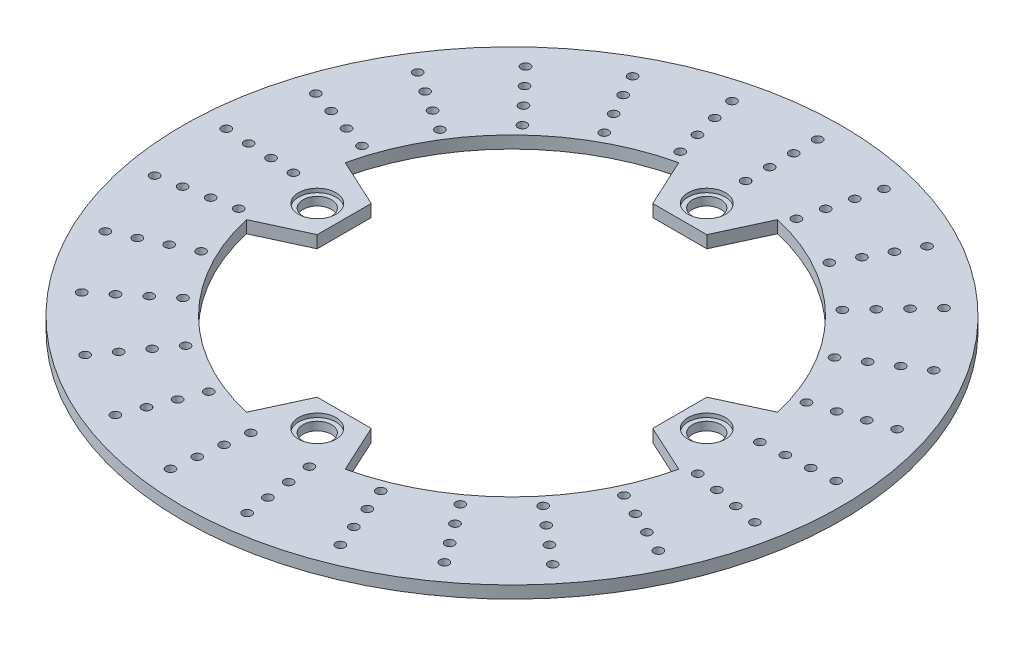
SolidWorks part; units mm, degrees
ref_plane "Front Plane" through (0, 0, 0) normal (0, 0, 1) x (1, 0, 0)
ref_plane "Top Plane" through (0, 0, 0) normal (0, 1, 0) x (1, 0, 0)
ref_plane "Right Plane" through (0, 0, 0) normal (1, 0, 0) x (0, 0, -1)
sketch "Sketch1" plane through (0, 0, 0) normal (0, 1, 0) x (1, 0, 0)
  line L0 (-9.02, 56) -> (9.02, 56)
  line L1 (9.02, 56) -> (16.4701, 72.1438)
  line L2 (-9.02, 56) -> (-16.4701, 72.1438)
  line L3 (0, 0) -> (0, 65) construction
  line L4 (56, 9.02) -> (72.1438, 16.4701)
  line L5 (56, 9.02) -> (56, -9.02)
  line L6 (56, -9.02) -> (72.1438, -16.4701)
  line L7 (9.02, -56) -> (16.4701, -72.1438)
  line L8 (9.02, -56) -> (-9.02, -56)
  line L9 (-9.02, -56) -> (-16.4701, -72.1438)
  line L10 (-56, -9.02) -> (-72.1438, -16.4701)
  line L11 (-56, -9.02) -> (-56, 9.02)
  line L12 (-56, 9.02) -> (-72.1438, 16.4701)
  circle A0 centre (0, 0) radius 110
  arc A1 (-16.4701, 72.1438) -> (-72.1438, 16.4701) centre (0, 0) ccw
  circle A2 centre (0, 65) radius 4.75
  circle A3 centre (65, 0) radius 4.75
  circle A4 centre (0, -65) radius 4.75
  circle A5 centre (-65, 0) radius 4.75
  arc A6 (72.1438, 16.4701) -> (16.4701, 72.1438) centre (0, 0) ccw
  arc A7 (-72.1438, -16.4701) -> (-16.4701, -72.1438) centre (0, 0) ccw
  arc A8 (16.4701, -72.1438) -> (72.1438, -16.4701) centre (0, 0) ccw
  point P6 (0, 0)
  point P10 (0, 0)
  point P11 (0, 56)
  point P34 (0, 0)
  dimension "D1" = 220
  dimension "D2" = 148
  dimension "D4" = 9.5
  dimension "D3" = 65
  dimension "D5" = 56
  dimension "D6" = 4
  dimension "D7" = 17.78
  dimension "D8" = 18.04
  dimension "D9" = 17.78
extrude "Boss-Extrude1" add sketch "Sketch1" along normal blind 4.1
sketch "Sketch3" plane through (0, 0, 0) normal (0, 1, 0) x (1, 0, 0)
  line L0 (0, 0) -> (0, 110) construction
  circle A0 centre (0, 0) radius 110 construction
  circle A1 centre (0, 102) radius 1.5
  circle A2 centre (0, 94) radius 1.5
  circle A3 centre (0, 86) radius 1.5
  circle A4 centre (0, 78) radius 1.5
  circle A6 centre (0, 70) radius 1.5 [skipped]
  dimension "D1" = 3
  dimension "D2" = 8
  dimension "D3" = 5
extrude "Cut-Extrude1" cut sketch "Sketch3" along normal blind 4.5
pattern_circular "CirPattern1" count 25 over 360 about axis through (0, 0, 0) along (0, 1, 0) of "Cut-Extrude1"
sketch "Sketch4" plane through (0, 4.1, 0) normal (0, 1, 0) x (1, 0, 0)
  circle A1 centre (0, 0) radius 110
  circle A2 centre (0, 0) radius 110
  circle A4 centre (0, 65) radius 6.25
  circle A5 centre (0, 65) radius 6.25
  dimension "D1" = 0
  dimension "D2" = 1.5
extrude "Cut-Extrude2" cut sketch "Sketch4" against normal blind 1.3 flip side to cut
pattern_circular "CirPattern2" count 4 over 360 about axis through (0, 0, 0) along (0, 1, 0) of "Cut-Extrude2"
